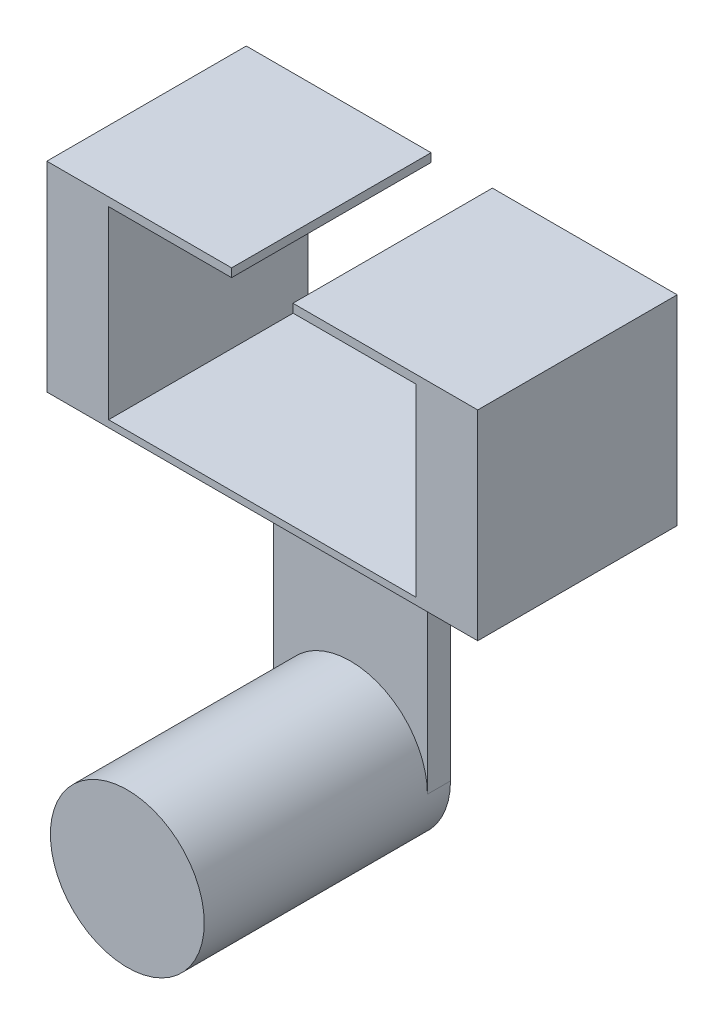
SolidWorks part; units mm, degrees
ref_plane "Front Plane" through (0, 0, 0) normal (0, 0, 1) x (1, 0, 0)
ref_plane "Top Plane" through (0, 0, 0) normal (0, 1, 0) x (1, 0, 0)
ref_plane "Right Plane" through (0, 0, 0) normal (1, 0, 0) x (0, 0, -1)
sketch "Sketch1" plane through (0, 0, 0) normal (0, 0, 1) x (1, 0, 0)
  circle A0 centre (0, 0) radius 15.875
  dimension "D1" = 31.75
extrude "Boss-Extrude1" add sketch "Sketch1" along normal blind 50.8
sketch "Sketch2" plane through (0, 0, 0) normal (0, 0, -1) x (-1, 0, 0)
  line L1 (-15.875, 0) -> (15.875, 0)
  line L2 (-15.875, 0) -> (-15.875, 50.8)
  line L3 (-15.875, 50.8) -> (15.875, 50.8)
  line L4 (15.875, 0) -> (15.875, 50.8)
  circle A0 centre (0, 0) radius 15.875 construction
  point P6 (0, 0)
  dimension "D1" = 50.8
  dimension "D2" = 31.75
extrude "Boss-Extrude2" add sketch "Sketch2" against normal blind 4.7625
sketch "Sketch3" plane through (0, 50.8, 0) normal (0, 1, 0) x (1, 0, 0)
  line L1 (-44.45, -22.9553) -> (44.45, -22.9553)
  line L2 (-44.45, -22.9553) -> (-44.45, 18.1928)
  line L3 (-44.45, 18.1928) -> (44.45, 18.1928)
  line L4 (44.45, -22.9553) -> (44.45, 18.1928)
  line L5 (-44.45, -22.9553) -> (44.45, 18.1928) construction
  line L6 (-44.45, 18.1928) -> (44.45, -22.9553) construction
  point P0 (0, -2.3812)
  dimension "D1" = 88.9
  dimension "D2" = 41.148
extrude "Boss-Extrude3" add sketch "Sketch3" along normal blind 41.2496
sketch "Sketch5" plane through (0, 0, 22.9553) normal (0, 0, 1) x (1, 0, 0)
  line L0 (-6.3246, 92.0496) -> (-6.3246, 90.297)
  line L1 (-44.45, 92.0496) -> (44.45, 92.0496) construction
  line L2 (-6.3246, 90.297) -> (-31.7043, 90.297)
  line L3 (-31.7043, 90.297) -> (-31.7043, 52.2224)
  line L4 (-31.7043, 52.2224) -> (31.7043, 52.2224)
  line L5 (31.7043, 52.2224) -> (31.7043, 90.297)
  line L6 (31.7043, 90.297) -> (6.3246, 90.297)
  line L7 (6.3246, 90.297) -> (6.3246, 92.0496)
  line L8 (6.3246, 92.0496) -> (-6.3246, 92.0496)
  line L9 (-44.45, 50.8) -> (44.45, 50.8) construction
  point P4 (0, 92.0496)
  point P11 (0, 52.2224)
  dimension "D1" = 38.0746
  dimension "D2" = 1.4224
  dimension "D3" = 25.3797
  dimension "D4" = 12.6492
  dimension "D5" = 38.0746
extrude "Cut-Extrude2" cut sketch "Sketch5" against normal through all
equation "\"D-pin\"= 1.13in"
equation "\"pin lenght\"= 2.00in"
equation "\"feature b Hight\"= 2in"
equation "\"Feathure b thickness\"= .14in"
equation "\"Brackect hight\"= 1.62in"
equation "\"brackect thickness\"= 1.62in"
equation "\"Top stem\"= 0.498in"
equation "\"flange\"= .9992in"
equation "\"lower cavity Height\"= 1.499"
